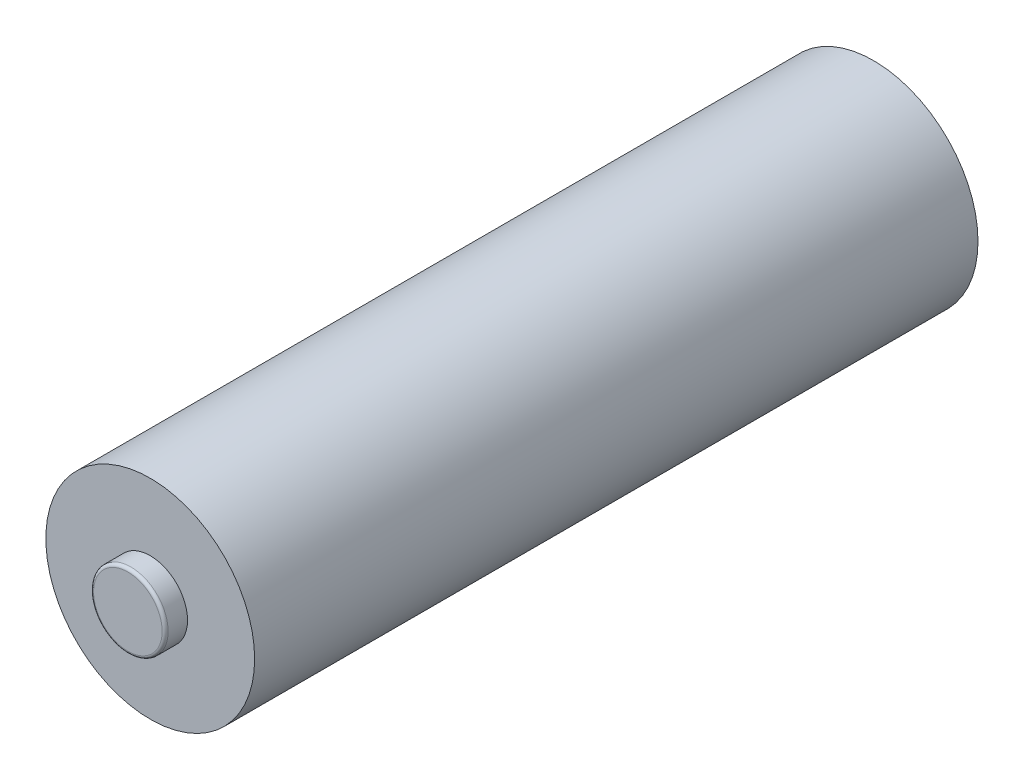
SolidWorks part; units mm, degrees
ref_plane "Front Plane" through (0, 0, 0) normal (0, 0, 1) x (1, 0, 0)
ref_plane "Top Plane" through (0, 0, 0) normal (0, 1, 0) x (1, 0, 0)
ref_plane "Right Plane" through (0, 0, 0) normal (1, 0, 0) x (0, 0, -1)
sketch "Sketch1" plane through (0, 0, 0) normal (0, 0, 1) x (1, 0, 0)
  circle A0 centre (0, 0) radius 7
extrude "Boss-Extrude1" add sketch "Sketch1" along normal blind 50
sketch "Sketch2" plane through (0, 0, 50) normal (0, 0, 1) x (1, 0, 0)
  circle A0 centre (0, 0) radius 2.5
  circle A1 centre (0, 0) radius 7
extrude "Cut-Extrude1" cut sketch "Sketch2" against normal blind 1.5
fillet "Fillet1" radius 0.2 1 edges at (2.5, 0, 50)
